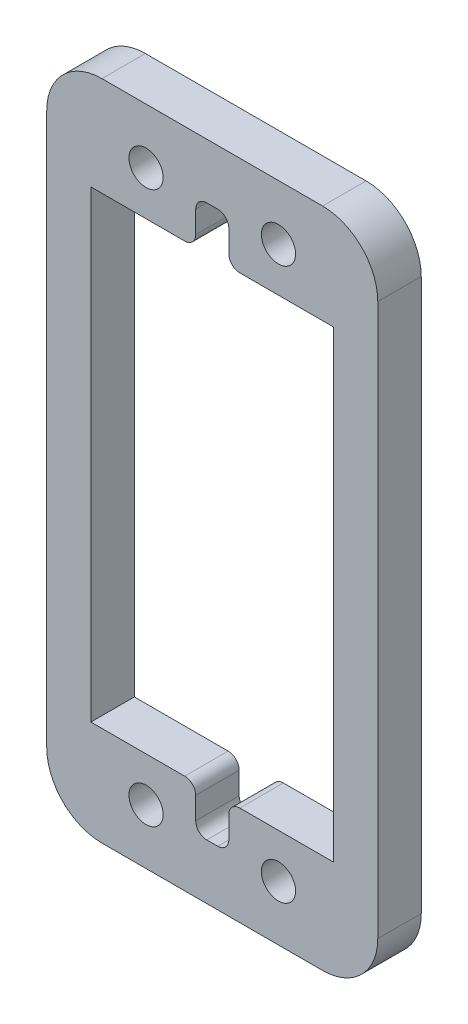
SolidWorks part; units mm, degrees
ref_plane "Alzado" through (0, 0, 0) normal (0, 0, 1) x (1, 0, 0)
ref_plane "Planta" through (0, 0, 0) normal (0, 1, 0) x (1, 0, 0)
ref_plane "Vista lateral" through (0, 0, 0) normal (1, 0, 0) x (0, 0, -1)
sketch "Croquis1" plane through (0, 0, 0) normal (0, 0, 1) x (1, 0, 0)
  line L0 (-15, 30) -> (15, 30)
  line L1 (15, 30) -> (15, -30)
  line L2 (15, -30) -> (-15, -30)
  line L3 (-15, -30) -> (-15, 30)
  line L4 (0, 0) -> (3.1755, 0) construction
  line L5 (0, 0) -> (0, 1.2752) construction
  dimension "D1" = 60
  dimension "D2" = 30
extrude "Saliente-Extruir1" add sketch "Croquis1" along normal blind 3.94
sketch "Croquis2" plane through (0, 0, 0) normal (0, 0, -1) x (-1, 0, 0)
  line L0 (-11, 21) -> (11, 21)
  line L1 (11, 21) -> (11, -21)
  line L2 (11, -21) -> (-11, -21)
  line L3 (-11, -21) -> (-11, 21)
  line L4 (0, 0) -> (17.9824, 0) construction
  line L5 (0, 0) -> (0, 11.2002) construction
  dimension "D1" = 22
  dimension "D2" = 42
extrude "Cortar-Extruir1" cut sketch "Croquis2" against normal through all
sketch "Croquis3" plane through (0, 0, 0) normal (0, 0, -1) x (-1, 0, 0)
  line L0 (0, 0) -> (-26.2125, 0) construction
  line L1 (0, 0) -> (0, 9.0898) construction
  line L2 (-1.5, 21) -> (-1.5, 25)
  line L3 (11, 21) -> (-11, 21) construction
  line L4 (-1.5, 25) -> (1.5, 25)
  line L5 (1.5, 25) -> (1.5, -25)
  line L6 (1.5, -25) -> (-1.5, -25)
  line L7 (-1.5, -25) -> (-1.5, 21)
  circle A0 centre (-6, 25) radius 1.55
  circle A1 centre (6, 25) radius 1.55
  circle A2 centre (-6, -25) radius 1.55
  circle A3 centre (6, -25) radius 1.55
  dimension "D1" = 3.1
  dimension "D2" = 3.1
  dimension "D3" = 3.1
  dimension "D4" = 3.1
  dimension "D5" = 12
  dimension "D6" = 12
  dimension "D7" = 50
  dimension "D8" = 25
  dimension "D9" = 3
  dimension "D10" = 50
extrude "Cortar-Extruir2" cut sketch "Croquis3" against normal through all
fillet "Redondeo1" radius 5 4 edges at (-15, -30, 1.97) (15, -30, 1.97) (15, 30, 1.97) (-15, 30, 1.97)
fillet "Redondeo3" radius 1 8 edges at (-1.5, -25, 1.97) (-1.5, -21, 1.97) (1.5, -21, 1.97) (1.5, -25, 1.97) (1.5, 25, 1.97) (-1.5, 25, 1.97) (1.5, 21, 1.97) (-1.5, 21, 1.97)
